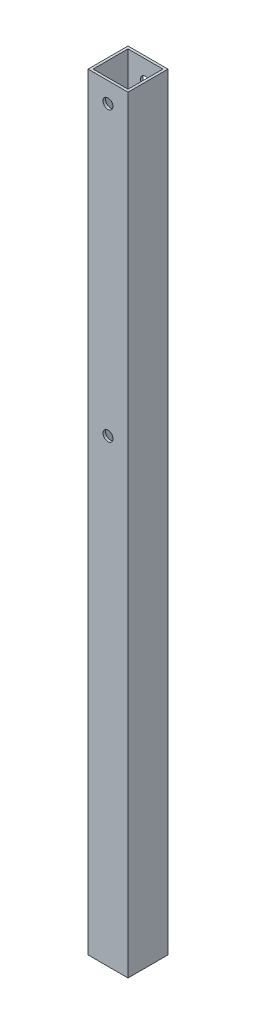
SolidWorks part; units mm, degrees
ref_plane "Front Plane" through (0, 0, 0) normal (0, 0, 1) x (1, 0, 0)
ref_plane "Top Plane" through (0, 0, 0) normal (0, 1, 0) x (1, 0, 0)
ref_plane "Right Plane" through (0, 0, 0) normal (1, 0, 0) x (0, 0, -1)
sketch "Sketch1" plane through (0, 0, 0) normal (0, 1, 0) x (1, 0, 0)
  line L1 (-12.7, -12.7) -> (12.7, -12.7)
  line L2 (-12.7, -12.7) -> (-12.7, 12.7)
  line L3 (-12.7, 12.7) -> (12.7, 12.7)
  line L4 (12.7, -12.7) -> (12.7, 12.7)
  line L5 (-12.7, -12.7) -> (12.7, 12.7) construction
  line L6 (-12.7, 12.7) -> (12.7, -12.7) construction
  line L7 (-11.1125, -11.1125) -> (11.1125, -11.1125)
  line L8 (-11.1125, -11.1125) -> (-11.1125, 11.1125)
  line L9 (-11.1125, 11.1125) -> (11.1125, 11.1125)
  line L10 (11.1125, -11.1125) -> (11.1125, 11.1125)
  line L11 (-11.1125, -11.1125) -> (11.1125, 11.1125) construction
  line L12 (-11.1125, 11.1125) -> (11.1125, -11.1125) construction
  point P0 (0, 0)
  point P6 (0, 0)
  dimension "D1" = 25.4
  dimension "D2" = 1.5875
extrude "Boss-Extrude1" add sketch "Sketch1" along normal blind 487.68
hole_wizard "1/4 (0.25) Diameter Hole1" positions "Sketch2" profile "Sketch4" hole size "1/4" standard "ANSI Inch" end condition through all
sketch "Sketch2" plane through (0, 0, 12.7) normal (0, 0, 1) x (1, 0, 0)
  line L0 (0, 487.68) -> (0, 0) construction
  line L1 (-12.7, 487.68) -> (12.7, 487.68) construction
  point P8 (0, 292.1)
  point P10 (0, 474.98)
  dimension "D1" = 292.1
  dimension "D2" = 182.88
sketch "Sketch4" plane through (0, 474.98, 12.7) normal (1, 0, 0) x (0, -1, 0)
  line L0 (0, 0) -> (0, 25.4)
  line L1 (0, 25.4) -> (3.175, 25.4)
  line L2 (3.175, 25.4) -> (3.175, 0)
  line L5 (3.175, 0) -> (0, 0)
  line L11 (0, -6.35) -> (0, 107.95) construction
  dimension "Thru Hole Dia." = 6.35
  dimension "Thru Hole Depth" = 25.4
